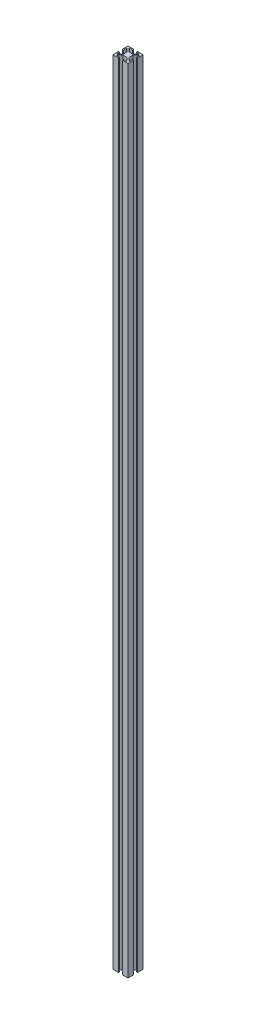
SolidWorks part; units mm, degrees
ref_plane "Plan de face" through (0, 0, 0) normal (0, 0, 1) x (1, 0, 0)
ref_plane "Plan de dessus" through (0, 0, 0) normal (0, 1, 0) x (1, 0, 0)
ref_plane "Plan de droite" through (0, 0, 0) normal (1, 0, 0) x (0, 0, -1)
sketch "Esquisse1" plane through (0, 0, 0) normal (0, 1, 0) x (1, 0, 0)
  line L0 (6.1245, 16.1036) -> (30.6226, 16.1036) construction
  line L6 (-11.5924, 0) -> (12.1076, 0) construction
  line L7 (0, 12.3466) -> (0, -12.7449) construction
  line L12 (-10, -10) -> (10, 10) construction
  line L59 (-10, -2.5) -> (-10, -10)
  line L60 (-10, -2.5) -> (-8.5, -2.5)
  line L69 (-8.5, -2.5) -> (-8.5, -6.2322)
  line L70 (-7.6464, -6.5858) -> (-3.75, -2.6893)
  line L73 (-6.5858, -7.6464) -> (-2.6893, -3.75)
  line L74 (-2.5, -8.5) -> (-6.2322, -8.5)
  line L75 (-2.5, -10) -> (-2.5, -8.5)
  line L76 (-2.5, -10) -> (-10, -10)
  line L77 (-2.5, 10) -> (-2.5, 8.5)
  line L78 (-2.5, 10) -> (-10, 10)
  line L79 (-10, 2.5) -> (-10, 10)
  line L80 (-10, 2.5) -> (-8.5, 2.5)
  line L81 (-8.5, 2.5) -> (-8.5, 6.2322)
  line L82 (-7.6464, 6.5858) -> (-3.75, 2.6893)
  line L83 (-6.5858, 7.6464) -> (-2.6893, 3.75)
  line L84 (-2.5, 8.5) -> (-6.2322, 8.5)
  line L85 (10, 2.5) -> (8.5, 2.5)
  line L86 (10, 2.5) -> (10, 10)
  line L87 (2.5, 10) -> (10, 10)
  line L88 (2.5, 10) -> (2.5, 8.5)
  line L89 (2.5, 8.5) -> (6.2322, 8.5)
  line L90 (6.5858, 7.6464) -> (2.6893, 3.75)
  line L91 (7.6464, 6.5858) -> (3.75, 2.6893)
  line L92 (8.5, 2.5) -> (8.5, 6.2322)
  line L93 (2.5, -10) -> (2.5, -8.5)
  line L94 (2.5, -10) -> (10, -10)
  line L95 (10, -2.5) -> (10, -10)
  line L96 (10, -2.5) -> (8.5, -2.5)
  line L97 (8.5, -2.5) -> (8.5, -6.2322)
  line L98 (7.6464, -6.5858) -> (3.75, -2.6893)
  line L99 (6.5858, -7.6464) -> (2.6893, -3.75)
  line L100 (2.5, -8.5) -> (6.2322, -8.5)
  line L101 (-3.75, 2.6893) -> (-3.75, -2.6893)
  line L102 (-2.6893, -3.75) -> (2.6893, -3.75)
  line L103 (-2.6893, 3.75) -> (2.6893, 3.75)
  line L104 (3.75, 2.6893) -> (3.75, -2.6893)
  arc A0 (-8.5, 6.2322) -> (-7.6464, 6.5858) centre (-8, 6.2322) cw
  arc A1 (-8.5, -6.2322) -> (-7.6464, -6.5858) centre (-8, -6.2322) ccw
  arc A2 (-6.5858, -7.6464) -> (-6.2322, -8.5) centre (-6.2322, -8) ccw
  arc A3 (6.5858, -7.6464) -> (6.2322, -8.5) centre (6.2322, -8) cw
  arc A4 (8.5, -6.2322) -> (7.6464, -6.5858) centre (8, -6.2322) cw
  arc A5 (7.6464, 6.5858) -> (8.5, 6.2322) centre (8, 6.2322) cw
  arc A6 (6.2322, 8.5) -> (6.5858, 7.6464) centre (6.2322, 8) cw
  arc A7 (-6.5858, 7.6464) -> (-6.2322, 8.5) centre (-6.2322, 8) cw
  point P7 (-2.5, -9.25)
  point P8 (2.5, -9.25)
  point P15 (-8.5, -7.4393)
  point P51 (0, 0)
  point P52 (-7.4393, -8.5)
  dimension "D2" = 5
  dimension "D7" = 0.5
  dimension "D1" = 20
  dimension "D3" = 4
  dimension "D4" = 7.5
  dimension "D5" = 1.5
  dimension "D6" = 1.5
extrude "Boss.-Extru.1" add sketch "Esquisse1" along normal blind 1050
